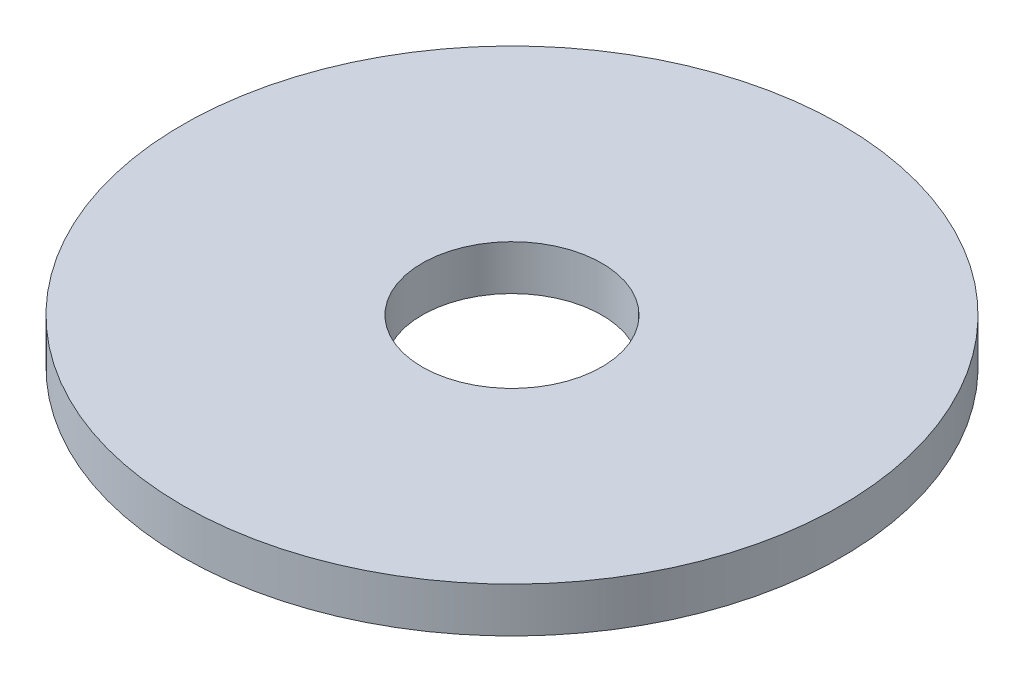
SolidWorks part; units mm, degrees
material "1060 Alloy"
ref_plane "Front Plane" through (0, 0, 0) normal (0, 0, 1) x (1, 0, 0)
ref_plane "Top Plane" through (0, 0, 0) normal (0, 1, 0) x (1, 0, 0)
ref_plane "Right Plane" through (0, 0, 0) normal (1, 0, 0) x (0, 0, -1)
sketch "Sketch1" plane through (0, 0, 0) normal (0, 1, 0) x (1, 0, 0)
  circle A0 centre (0, 0) radius 3
  circle A1 centre (0, 0) radius 11
extrude "Boss-Extrude1" add sketch "Sketch1" along normal blind 1.5
